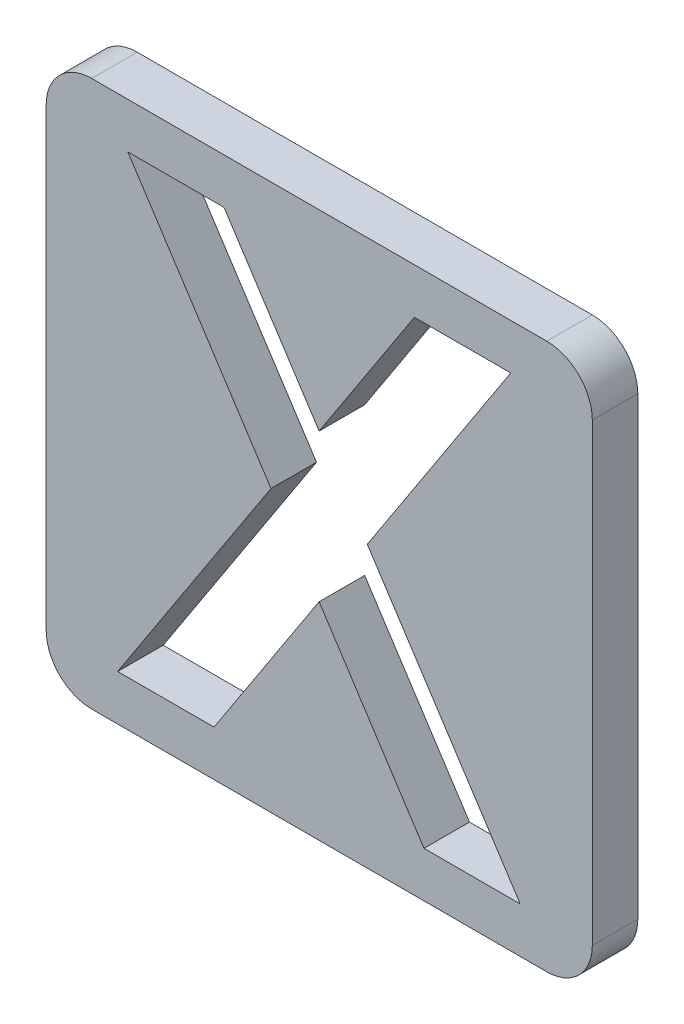
SolidWorks part; units mm, degrees
ref_plane "Front Plane" through (0, 0, 0) normal (0, 0, 1) x (1, 0, 0)
ref_plane "Top Plane" through (0, 0, 0) normal (0, 1, 0) x (1, 0, 0)
ref_plane "Right Plane" through (0, 0, 0) normal (1, 0, 0) x (0, 0, -1)
sketch "Sketch1" plane through (0, 0, 0) normal (0, 0, 1) x (1, 0, 0)
  line L1 (-50, 60) -> (50, 60)
  line L2 (-60, 50) -> (-60, -50)
  line L3 (-50, -60) -> (50, -60)
  line L4 (60, 50) -> (60, -50)
  line L5 (-60, 60) -> (60, -60) construction
  line L6 (-60, -60) -> (60, 60) construction
  arc A0 (-60, -50) -> (-50, -60) centre (-50, -50) ccw
  arc A1 (50, -60) -> (60, -50) centre (50, -50) ccw
  arc A2 (50, 60) -> (60, 50) centre (50, 50) cw
  arc A3 (-50, 60) -> (-60, 50) centre (-50, 50) ccw
  point P0 (0, 0)
  dimension "D3" = 10
  dimension "D1" = 120
  dimension "D2" = 120
extrude "Boss-Extrude1" add sketch "Sketch1" along normal blind 10 contours A3 L2 A0 L3 A1 L4 A2 L1
sketch "Sketch2" plane through (0, 0, 10) normal (0, 0, 1) x (1, 0, 0)
  line L0 (0, 0) -> (0, 40) construction
  line L1 (-50, 50) -> (50, 50) construction
  line L2 (-50, 50) -> (-50, -50) construction
  line L3 (-50, -50) -> (50, -50) construction
  line L4 (50, 50) -> (50, -50) construction
  line L5 (-50, 50) -> (50, -50) construction
  line L6 (-50, -50) -> (50, 50) construction
  line L7 (0, 40) -> (-40, 40) construction
  line L8 (-40, 40) -> (-40, 0) construction
  line L9 (-40, 0) -> (0, 0) construction
  line L11 (0, 20) -> (-20, 20) construction
  line L12 (-20, 40) -> (-20, 20) construction
  circle A0 centre (0, 40) radius 4 construction
  circle A1 centre (0, 20) radius 4 construction
  circle A2 centre (0, 0) radius 4 construction
  circle A3 centre (-20, 20) radius 4 construction
  circle A4 centre (-20, 40) radius 4 construction
  circle A5 centre (-40, 40) radius 4 construction
  circle A6 centre (0, 0) radius 4 construction
  circle A7 centre (20, 0) radius 4 construction
  circle A8 centre (40, 0) radius 4 construction
  circle A9 centre (40, 20) radius 4 construction
  circle A10 centre (40, 40) radius 4 construction
  circle A11 centre (20, 20) radius 4 construction
  circle A12 centre (0, 0) radius 4 construction
  circle A13 centre (0, -20) radius 4 construction
  circle A14 centre (0, -40) radius 4 construction
  circle A15 centre (20, -40) radius 4 construction
  circle A16 centre (40, -40) radius 4 construction
  circle A17 centre (20, -20) radius 4 construction
  circle A18 centre (0, 0) radius 4 construction
  circle A19 centre (-20, 0) radius 4 construction
  circle A20 centre (-40, 0) radius 4 construction
  circle A21 centre (-40, -20) radius 4 construction
  circle A22 centre (-40, -40) radius 4 construction
  circle A23 centre (-20, -20) radius 4 construction
  text T0 "X" font "Century Gothic" height 100
  point P0 (0, 0)
  point P55 (0, 0)
  dimension "D4" = 8
  dimension "D1" = 100
  dimension "D2" = 100
  dimension "D3" = 40
  dimension "D5" = 4
extrude "Cut-Extrude37" cut sketch "Sketch2" against normal blind 10
